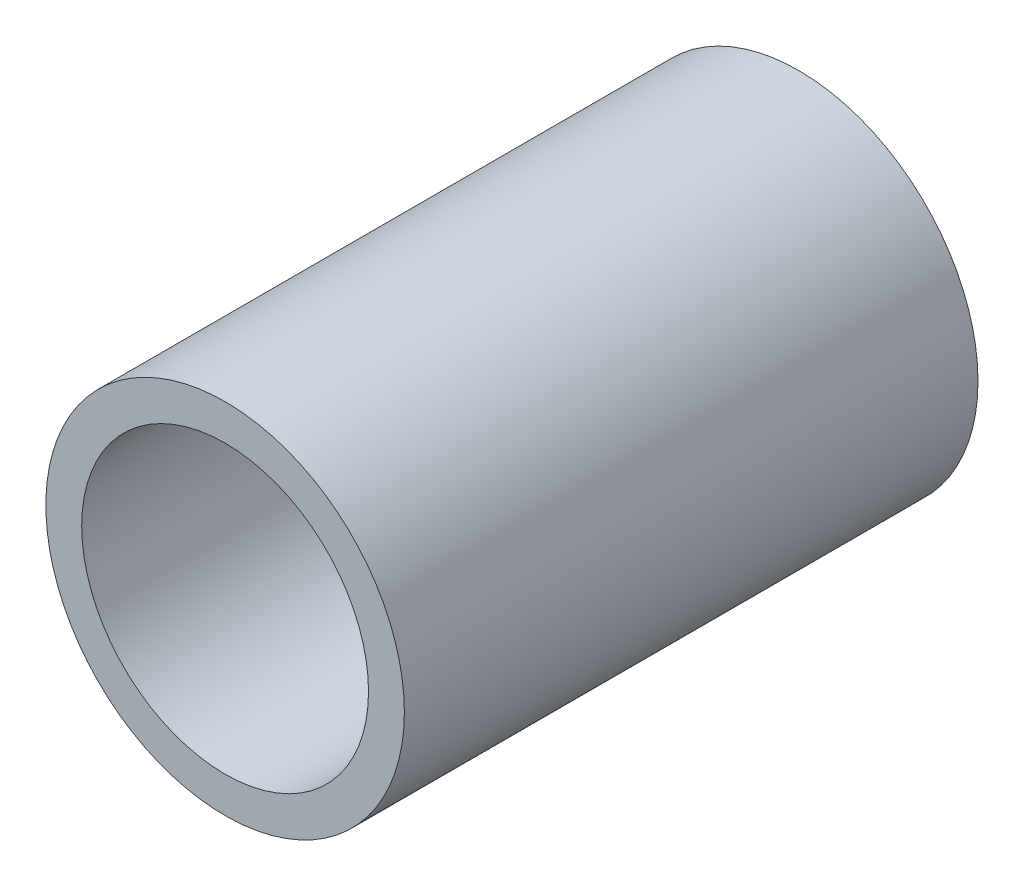
SolidWorks part; units mm, degrees
ref_plane "Front Plane" through (0, 0, 0) normal (0, 0, 1) x (1, 0, 0)
ref_plane "Top Plane" through (0, 0, 0) normal (0, 1, 0) x (1, 0, 0)
ref_plane "Right Plane" through (0, 0, 0) normal (1, 0, 0) x (0, 0, -1)
sketch "Sketch1" plane through (0, 0, 0) normal (0, 0, 1) x (1, 0, 0)
  circle A0 centre (-3.474, 0) radius 0.635
  circle A1 centre (-3.474, 0) radius 0.508
extrude "Boss-Extrude1" add sketch "Sketch1" against normal blind 2.032
